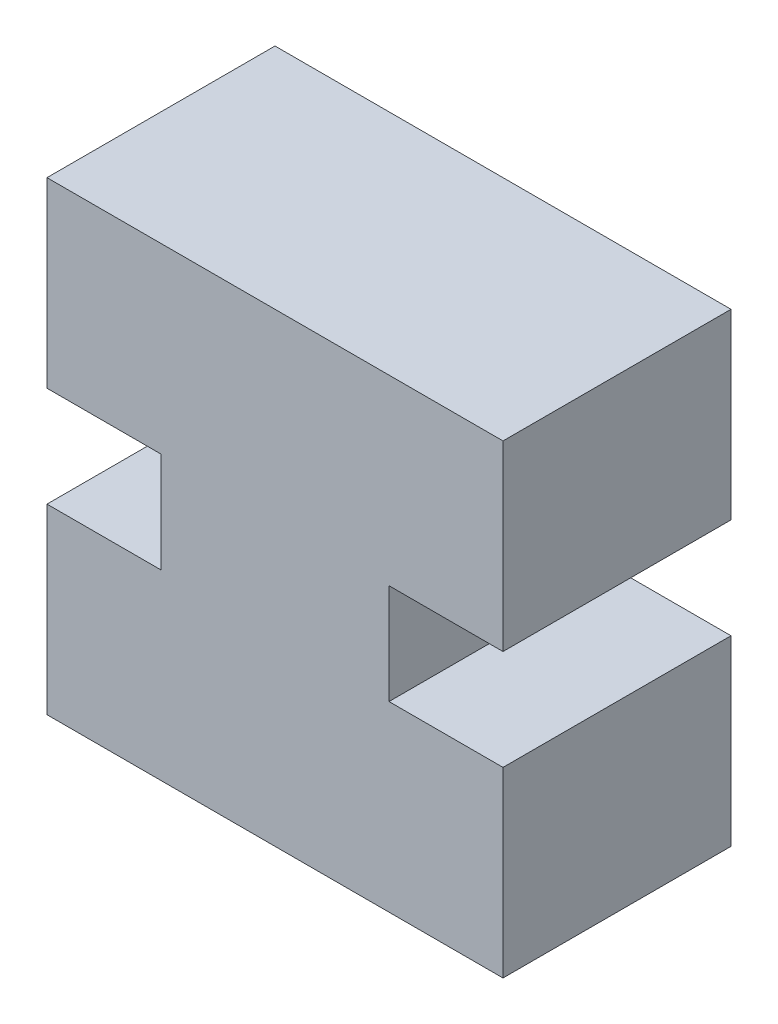
SolidWorks part; units mm, degrees
ref_plane "Front Plane" through (0, 0, 0) normal (0, 0, 1) x (1, 0, 0)
ref_plane "Top Plane" through (0, 0, 0) normal (0, 1, 0) x (1, 0, 0)
ref_plane "Right Plane" through (0, 0, 0) normal (1, 0, 0) x (0, 0, -1)
sketch "Sketch2" plane through (0, 0, 0) normal (0, 0, 1) x (1, 0, 0)
  line L0 (0, 0) -> (12.7, 0)
  line L1 (12.7, 0) -> (12.7, -5.08)
  line L2 (12.7, -5.08) -> (9.525, -5.08)
  line L3 (9.525, -5.08) -> (9.525, -7.874)
  line L4 (9.525, -7.874) -> (12.7, -7.874)
  line L5 (12.7, -7.874) -> (12.7, -12.954)
  line L6 (12.7, -12.954) -> (0, -12.954)
  line L7 (0, -12.954) -> (0, -7.874)
  line L8 (0, -7.874) -> (3.175, -7.874)
  line L9 (3.175, -7.874) -> (3.175, -5.08)
  line L10 (3.175, -5.08) -> (0, -5.08)
  line L11 (0, -5.08) -> (0, 0)
  dimension "D1" = 12.7
  dimension "D2" = 12.7
  dimension "D3" = 5.08
  dimension "D4" = 2.794
  dimension "D5" = 5.08
  dimension "D6" = 2.794
  dimension "D7" = 7.874
  dimension "D8" = 3.175
  dimension "D9" = 3.175
extrude "Boss-Extrude1" add sketch "Sketch2" along normal blind 6.35
